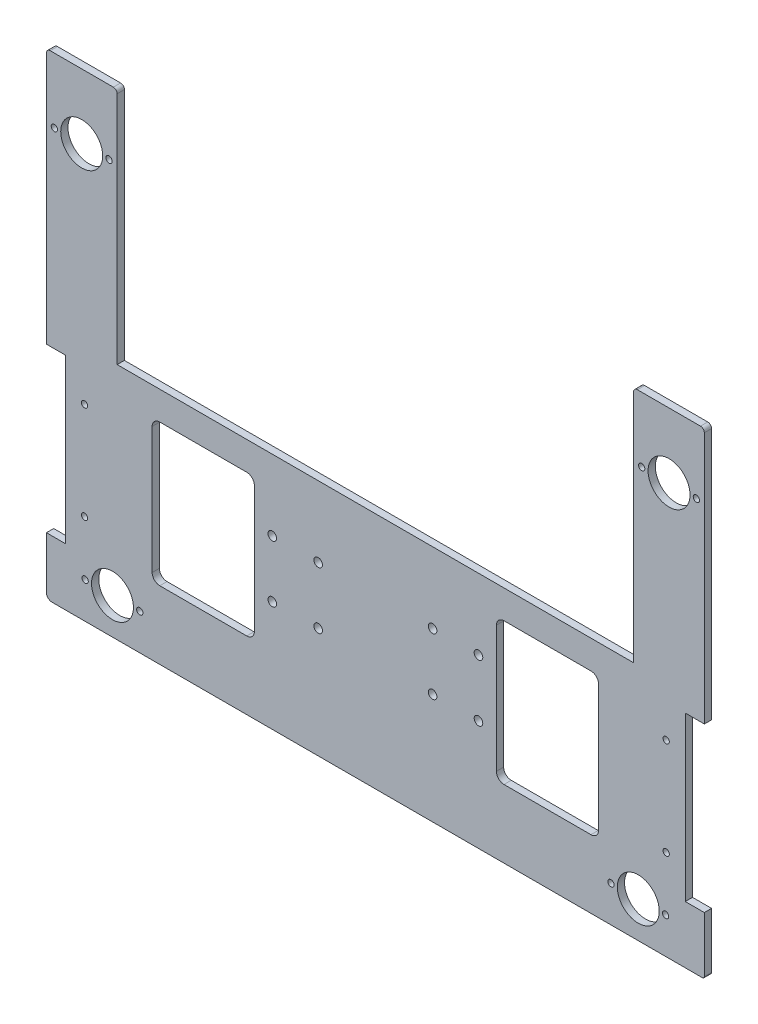
SolidWorks part; units mm, degrees
ref_plane "Front Plane" through (0, 0, 0) normal (0, 0, 1) x (1, 0, 0)
ref_plane "Top Plane" through (0, 0, 0) normal (0, 1, 0) x (1, 0, 0)
ref_plane "Right Plane" through (0, 0, 0) normal (1, 0, 0) x (0, 0, -1)
ref_plane "Plane1" through (0, 150, 0) normal (0, 1, 0) x (1, 0, 0)
ref_plane "Plane2" through (0, -150, 0) normal (0, 1, 0) x (1, 0, 0)
ref_plane "Plane3" through (150, 0, 0) normal (1, 0, 0) x (0, 0, -1)
ref_plane "Plane4" through (-150, 0, 0) normal (1, 0, 0) x (0, 0, -1)
sketch "Sketch2" plane through (0, 0, 0) normal (0, 0, 1) x (1, 0, 0)
  line L0 (0, -10.2) -> (0, 50.0764) construction
  line L5 (-54.06, -12.1397) -> (-54.06, -42.0297) construction
  line L23 (-170.5, 150) -> (-137.4, 150)
  line L24 (139.6652, 116) -> (168.3348, 116) construction
  line L30 (-172.5, 148) -> (-172.5, 15.7195)
  line L31 (-169.5, -100) -> (171.5, -100)
  line L39 (172.5, 148) -> (172.5, 15.7195)
  line L40 (-152.1866, -81.0661) -> (-123.5266, -81.0661) construction
  line L42 (-135.4, 148) -> (-135.4, 25)
  line L43 (-135.4, 25) -> (135.4, 25)
  line L44 (135.4, 148) -> (135.4, 25)
  line L45 (137.4, 150) -> (170.5, 150)
  line L47 (-67.4574, 10.0867) -> (-113.0552, 10.0867)
  line L48 (67.4574, 10.0867) -> (113.0552, 10.0867)
  line L49 (63.4574, 6.0867) -> (63.4574, -60.2561)
  line L50 (67.4574, -64.2561) -> (113.0552, -64.2561)
  line L51 (117.0552, 6.0867) -> (117.0552, -60.2561)
  line L52 (63.4574, 10.0867) -> (117.0552, -64.2561) construction
  line L53 (63.4574, -64.2561) -> (117.0552, 10.0867) construction
  line L54 (-63.4574, 6.0867) -> (-63.4574, -60.2561)
  line L55 (-67.4574, -64.2561) -> (-113.0552, -64.2561)
  line L56 (-117.0552, 6.0867) -> (-117.0552, -60.2561)
  line L57 (177.1787, -66.0847) -> (177.1787, 11.9153) construction
  line L61 (162.5, 15.7195) -> (162.5, -69.8889)
  line L62 (162.5, -69.8889) -> (172.5, -69.8889)
  line L63 (172.5, 15.7195) -> (162.5, 15.7195)
  line L65 (172.5, -69.8889) -> (172.5, -99)
  line L66 (177.1787, 0) -> (1253.7576, 0) construction
  line L67 (-162.5, 15.7195) -> (-162.5, -69.8889)
  line L69 (-172.5, -69.8889) -> (-172.5, -97)
  line L70 (-152.5, -1.5847) -> (-152.5, -52.5847) construction
  line L71 (-172.5, 15.7195) -> (-162.5, 15.7195)
  line L72 (-172.5, -69.8889) -> (-162.5, -69.8889)
  circle A1 centre (-168.3348, 116) radius 1.65
  circle A2 centre (-139.6652, 116) radius 1.65
  circle A3 centre (168.3348, 116) radius 1.65
  circle A4 centre (139.6652, 116) radius 1.65
  circle A9 centre (154, 116) radius 11
  circle A10 centre (-154, 116) radius 11
  circle A17 centre (152.5, -52.5847) radius 1.65
  circle A18 centre (152.5, -1.5847) radius 1.65
  circle A19 centre (-152.5, -52.5847) radius 1.65
  circle A20 centre (-152.5, -1.5847) radius 1.65
  circle A27 centre (-30, -42.0297) radius 2.25
  circle A32 centre (-30, -12.1397) radius 2.25
  circle A33 centre (-54.06, -12.1397) radius 2.25
  circle A34 centre (-54.06, -42.0297) radius 2.25
  circle A35 centre (54.06, -42.0297) radius 2.25
  circle A36 centre (30, -42.0297) radius 2.25
  circle A37 centre (30, -12.1397) radius 2.25
  circle A38 centre (54.06, -12.1397) radius 2.25
  circle A39 centre (-123.5266, -81.0661) radius 1.65
  circle A40 centre (-152.1866, -81.0661) radius 1.65
  circle A41 centre (-137.8566, -81.0661) radius 11
  arc A42 (-170.5, 150) -> (-172.5, 148) centre (-170.5, 148) ccw
  arc A43 (170.5, 150) -> (172.5, 148) centre (170.5, 148) cw
  arc A45 (-172.5, -97) -> (-169.5, -100) centre (-169.5, -97) ccw
  arc A46 (135.4, 148) -> (137.4, 150) centre (137.4, 148) cw
  arc A47 (-135.4, 148) -> (-137.4, 150) centre (-137.4, 148) ccw
  arc A48 (63.4574, -60.2561) -> (67.4574, -64.2561) centre (67.4574, -60.2561) ccw
  arc A49 (113.0552, -64.2561) -> (117.0552, -60.2561) centre (113.0552, -60.2561) ccw
  arc A50 (113.0552, 10.0867) -> (117.0552, 6.0867) centre (113.0552, 6.0867) cw
  arc A51 (67.4574, 10.0867) -> (63.4574, 6.0867) centre (67.4574, 6.0867) ccw
  arc A52 (-113.0552, 10.0867) -> (-117.0552, 6.0867) centre (-113.0552, 6.0867) ccw
  arc A53 (-67.4574, 10.0867) -> (-63.4574, 6.0867) centre (-67.4574, 6.0867) cw
  arc A54 (-63.4574, -60.2561) -> (-67.4574, -64.2561) centre (-67.4574, -60.2561) cw
  arc A55 (-113.0552, -64.2561) -> (-117.0552, -60.2561) centre (-113.0552, -60.2561) cw
  arc A64 (172.5, -99) -> (171.5, -100) centre (171.5, -99) cw
  circle A65 centre (123.5266, -81.0661) radius 1.65
  circle A66 centre (152.1866, -81.0661) radius 1.65
  circle A67 centre (137.8566, -81.0661) radius 11
  point P0 (0, 0)
  point P2 (0, 0)
  point P4 (0, 150)
  point P11 (-152.5, -27.0847)
  point P12 (90.2563, -27.0847)
  point P39 (-162.5, -27.0847)
  point P45 (135.4, 150)
  point P82 (177.1787, -27.0847)
  point P103 (0, 0)
  point P104 (0, 0)
  point P107 (0, 0)
  point P109 (0, 0)
  point P110 (0, 0)
  point P111 (-117.0552, -27.0847)
  point P113 (0, 0)
  point P115 (-23.794, -72.0971)
  point P116 (-95.8742, -80.9002)
  point P118 (-141.4351, -82.6945)
  point P119 (0, 0)
  point P121 (-137.8566, -81.0661)
  point P131 (-54.06, -27.0847)
  point P132 (-63.4574, -27.0847)
  dimension "D3" = 51
  dimension "D7" = 34
  dimension "D8" = 3.3
  dimension "D9" = 18.5
  dimension "D10" = 22
  dimension "D11" = 74.3428
  dimension "D12" = 135.4
  dimension "D13" = 53.5977
  dimension "D16" = 14.33
  dimension "D17" = 22
  dimension "D18" = 2
  dimension "D19" = 3.3
  dimension "D6" = 14.3348
  dimension "D20" = 14.3348
  dimension "D21" = 2
  dimension "D23" = 4.5
  dimension "D24" = 4.5
  dimension "D25" = 4.5
  dimension "D26" = 4.5
  dimension "D27" = 29.89
  dimension "D29" = 24.06
  dimension "D31" = 4
  dimension "D32" = 10
  dimension "D33" = 1
  dimension "D34" = 135.4
  dimension "D35" = 85.6084
  dimension "D4" = 3.3
  dimension "D5" = 10
  dimension "D22" = 29.89
  dimension "D28" = 24.06
  dimension "D30" = 30
  dimension "D14" = 125
  dimension "D15" = 14.33
extrude "Boss-Extrude1" add sketch "Sketch2" along normal blind 3.8
